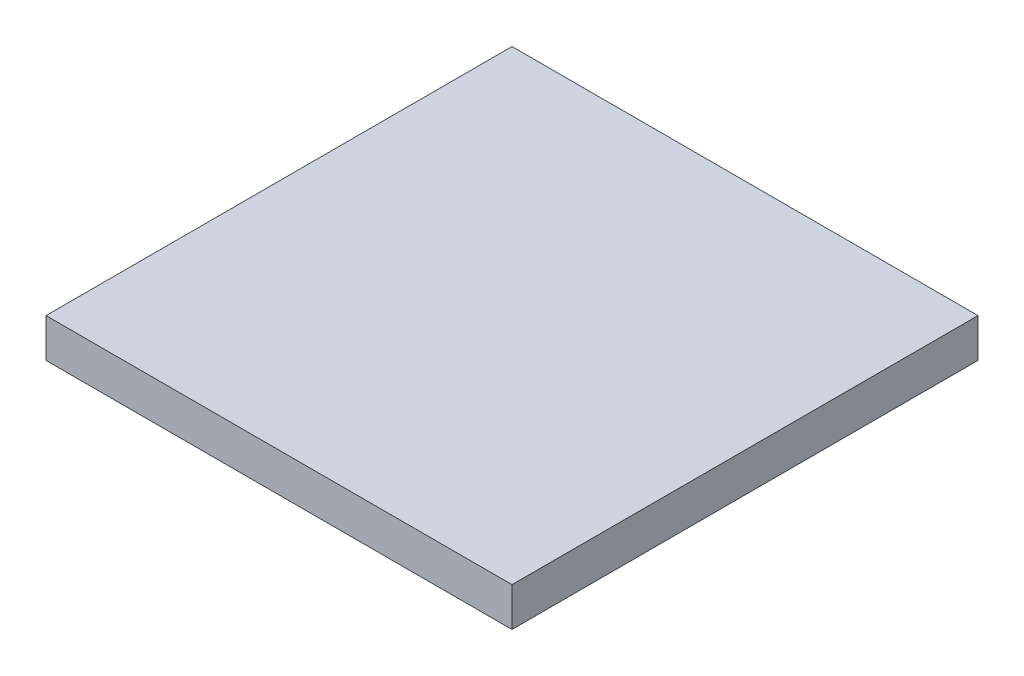
SolidWorks part; units mm, degrees
ref_plane "Front Plane" through (0, 0, 0) normal (0, 0, 1) x (1, 0, 0)
ref_plane "Top Plane" through (0, 0, 0) normal (0, 1, 0) x (1, 0, 0)
ref_plane "Right Plane" through (0, 0, 0) normal (1, 0, 0) x (0, 0, -1)
sketch "Sketch1" plane through (0, 0, 0) normal (0, 1, 0) x (1, 0, 0)
  line L1 (-30, -30) -> (30, -30)
  line L2 (-30, -30) -> (-30, 30)
  line L3 (-30, 30) -> (30, 30)
  line L4 (30, -30) -> (30, 30)
  line L5 (-30, -30) -> (30, 30) construction
  line L6 (-30, 30) -> (30, -30) construction
  point P0 (0, 0)
  dimension "D1" = 60
  dimension "D2" = 60
extrude "Boss-Extrude1" add sketch "Sketch1" along normal blind 5
